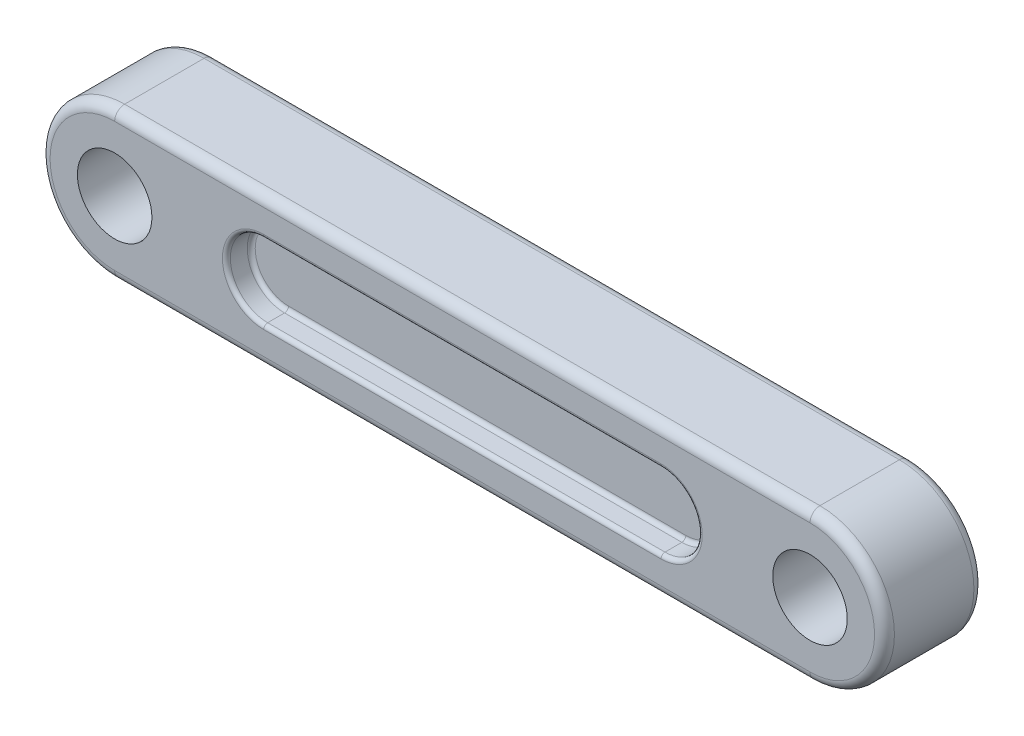
SolidWorks part; units mm, degrees
material "ABS"
ref_plane "Front Plane" through (0, 0, 0) normal (0, 0, 1) x (1, 0, 0)
ref_plane "Top Plane" through (0, 0, 0) normal (0, 1, 0) x (1, 0, 0)
ref_plane "Right Plane" through (0, 0, 0) normal (1, 0, 0) x (0, 0, -1)
sketch "Sketch1" plane through (0, 0, 0) normal (0, 0, 1) x (1, 0, 0)
  line L0 (-44.45, 0) -> (44.45, 0) construction
  line L1 (-44.45, 9.525) -> (44.45, 9.525)
  line L2 (-44.45, -9.525) -> (44.45, -9.525)
  line L3 (-53.975, 0) -> (-44.45, 0) construction
  line L4 (53.975, 0) -> (44.45, 0) construction
  arc A0 (-44.45, 9.525) -> (-44.45, -9.525) centre (-44.45, 0) ccw
  arc A1 (44.45, -9.525) -> (44.45, 9.525) centre (44.45, 0) ccw
  circle A2 centre (-44.45, 0) radius 4.7625
  circle A3 centre (44.45, 0) radius 4.7625
  point P2 (0, 0)
  dimension "D3" = 9.525
  dimension "D4" = 9.525
  dimension "D1" = 19.05
  dimension "D2" = 88.9
extrude "Boss-Extrude1" add sketch "Sketch1" along normal blind 12.7
fillet "Fillet1" radius 1.27 8 edges at (-53.975, 0, 0) (0, -9.525, 0) (0, 9.525, 0) (53.975, 0, 0) (53.975, 0, 12.7) (0, -9.525, 12.7) (-53.975, 0, 12.7) (0, 9.525, 12.7)
sketch "Sketch2" plane through (0, 0, 12.7) normal (0, 0, 1) x (1, 0, 0)
  line L0 (-44.45, 0) -> (44.45, 0) construction
  line L1 (-25.4, 0) -> (25.4, 0) construction
  line L2 (-25.4, 4.7625) -> (25.4, 4.7625)
  line L3 (-25.4, -4.7625) -> (25.4, -4.7625)
  arc A0 (-25.4, 4.7625) -> (-25.4, -4.7625) centre (-25.4, 0) ccw
  arc A1 (25.4, -4.7625) -> (25.4, 4.7625) centre (25.4, 0) ccw
  point P6 (0, 0)
  dimension "D3" = 9.525
  dimension "D1" = 19.05
  dimension "D2" = 19.05
extrude "Cut-Extrude1" cut sketch "Sketch2" against normal blind 3.175
sketch "Sketch3" plane through (0, 0, 0) normal (0, 0, -1) x (-1, 0, 0)
  line L0 (44.45, 0) -> (-44.45, 0) construction
  line L1 (25.4, 0) -> (-25.4, 0) construction
  line L2 (25.4, -4.7625) -> (-25.4, -4.7625)
  line L3 (25.4, 4.7625) -> (-25.4, 4.7625)
  arc A0 (25.4, -4.7625) -> (25.4, 4.7625) centre (25.4, 0) ccw
  arc A1 (-25.4, 4.7625) -> (-25.4, -4.7625) centre (-25.4, 0) ccw
  point P6 (0, 0)
  dimension "D2" = 19.05
  dimension "D1" = 9.525
  dimension "D3" = 19.05
extrude "Cut-Extrude2" cut sketch "Sketch3" against normal blind 3.175
fillet "Fillet3" radius 0.508 16 edges at (0, 4.7625, 3.175) (0, 4.7625, 0) (-30.1625, 0, 3.175) (-30.1625, 0, 0) (30.1625, 0, 3.175) (30.1625, 0, 0) (0, -4.7625, 3.175) (0, -4.7625, 0) (0, -4.7625, 9.525) (0, -4.7625, 12.7) (30.1625, 0, 9.525) (30.1625, 0, 12.7) (-30.1625, 0, 9.525) (-30.1625, 0, 12.7) (0, 4.7625, 9.525) (0, 4.7625, 12.7)
equation "\"ShaftD\"= 3 / 8"
equation "\"D4@Sketch1\"=\"ShaftD\""
equation "\"D3@Sketch1\"=\"ShaftD\""
equation "\"Width\"=0.75"
equation "\"D1@Sketch1\"=\"Width\""
equation "\"lengthW2W\"=3.5"
equation "\"D2@Sketch1\"=\"lengthW2W\""
equation "\"OverallThickness\"= 0.5"
equation "\"D1@Boss-Extrude1\"=\"OverallThickness\""
equation "\"D1@Sketch2\"=\"ShaftD\"*2"
equation "\"D2@Sketch2\"=\"ShaftD\"*2"
equation "\"D3@Sketch2\"=\"Width\"/2"
equation "\"D1@Cut-Extrude1\"=\"OverallThickness\"/4"
equation "\"D1@Sketch3\"=\"Width\"/2"
equation "\"D2@Sketch3\"=\"ShaftD\"*2"
equation "\"D3@Sketch3\"=\"ShaftD\"*2"
equation "\"D1@Cut-Extrude2\"=\"OverallThickness\"/4"
equation "\"OuterFillet\"= 0.05"
equation "\"InnerFillet\"= 0.02"
equation "\"D1@Fillet3\"=\"InnerFillet\""
equation "\"D1@Fillet1\"=\"OuterFillet\""
